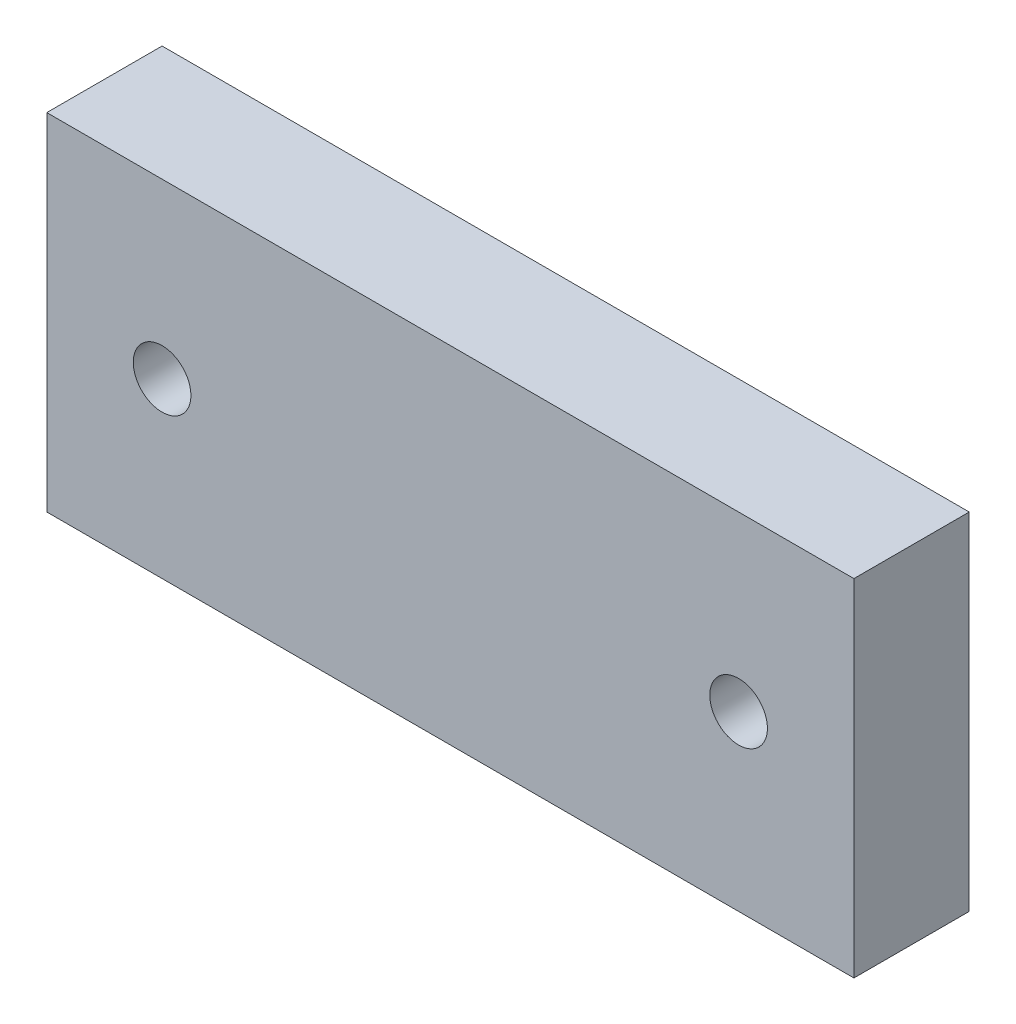
SolidWorks part; units mm, degrees
ref_plane "Alzado" through (0, 0, 0) normal (0, 0, 1) x (1, 0, 0)
ref_plane "Planta" through (0, 0, 0) normal (0, 1, 0) x (1, 0, 0)
ref_plane "Vista lateral" through (0, 0, 0) normal (1, 0, 0) x (0, 0, -1)
sketch "Croquis1" plane through (0, 0, 0) normal (0, 0, 1) x (1, 0, 0)
  line L1 (-30.4122, 13.3566) -> (-2.4122, 13.3566)
  line L2 (-30.4122, 13.3566) -> (-30.4122, 1.3566)
  line L3 (-30.4122, 1.3566) -> (-2.4122, 1.3566)
  line L4 (-2.4122, 13.3566) -> (-2.4122, 1.3566)
  dimension "D1" = 28
  dimension "D2" = 12
extrude "Saliente-Extruir1" add sketch "Croquis1" along normal blind 4
sketch "Croquis2" plane through (0, 0, 4) normal (0, 0, 1) x (1, 0, 0)
  line L1 (-2.4122, 1.3566) -> (-2.4122, 13.3566) construction
  line L2 (-30.4122, 1.3566) -> (-2.4122, 1.3566) construction
  circle A0 centre (-26.4122, 7.3566) radius 1
  circle A1 centre (-6.4122, 7.3566) radius 1
  dimension "D1" = 20
  dimension "D2" = 6
  dimension "D3" = 4
extrude "Cortar-Extruir1" cut sketch "Croquis2" against normal up to vertex (4 mm away)
